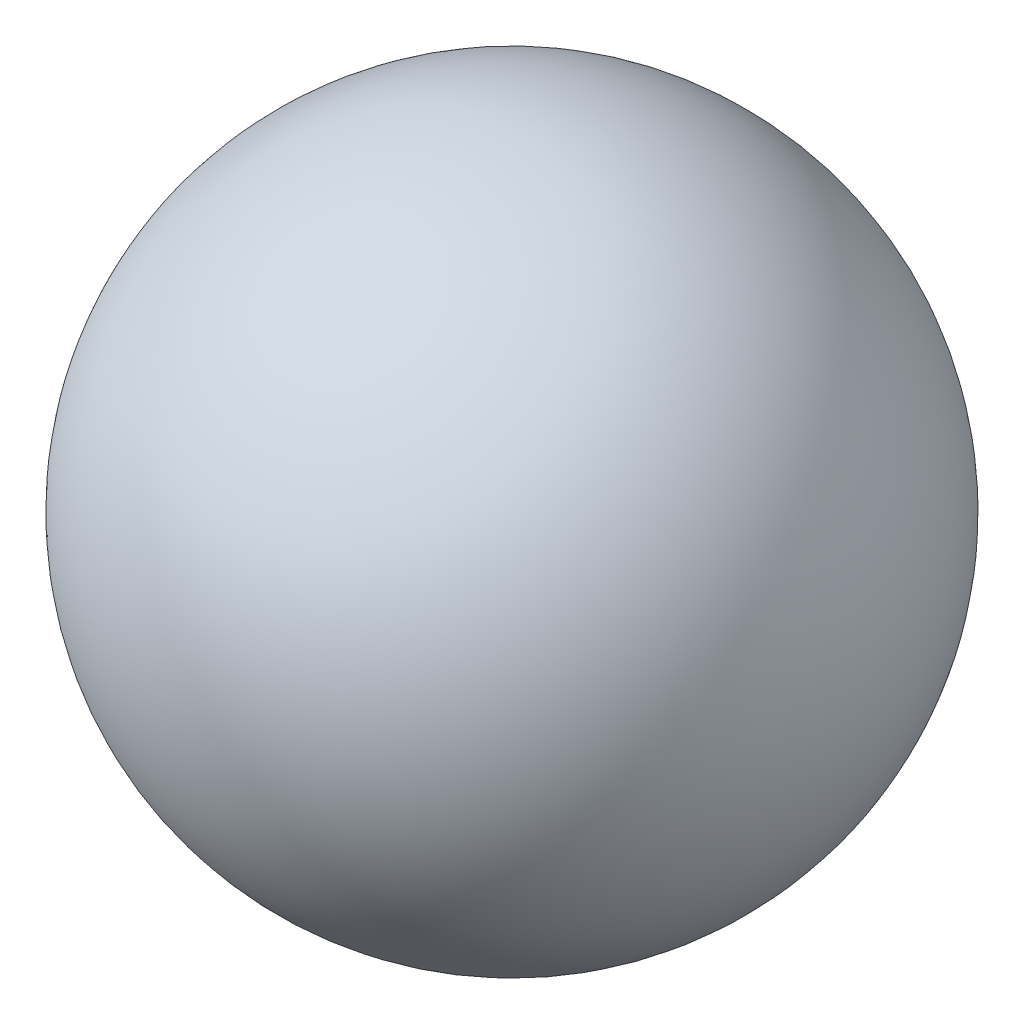
SolidWorks part; units mm, degrees
material "AISI 4340 Acier normalisé"
ref_plane "Face" through (0, 0, 0) normal (0, 0, 1) x (1, 0, 0)
ref_plane "Dessus" through (0, 0, 0) normal (0, 1, 0) x (1, 0, 0)
ref_plane "Droite" through (0, 0, 0) normal (1, 0, 0) x (0, 0, -1)
sketch "Esquisse1" plane through (0, 0, 0) normal (0, 0, 1) x (1, 0, 0)
  line L0 (-0.75, 0) -> (0.75, 0)
  arc A0 (-0.75, 0) -> (0.75, 0) centre (0, 0) cw
  dimension "D1" = 0.75
revolve "Révolution1" add sketch "Esquisse1" angle 360 about L0
